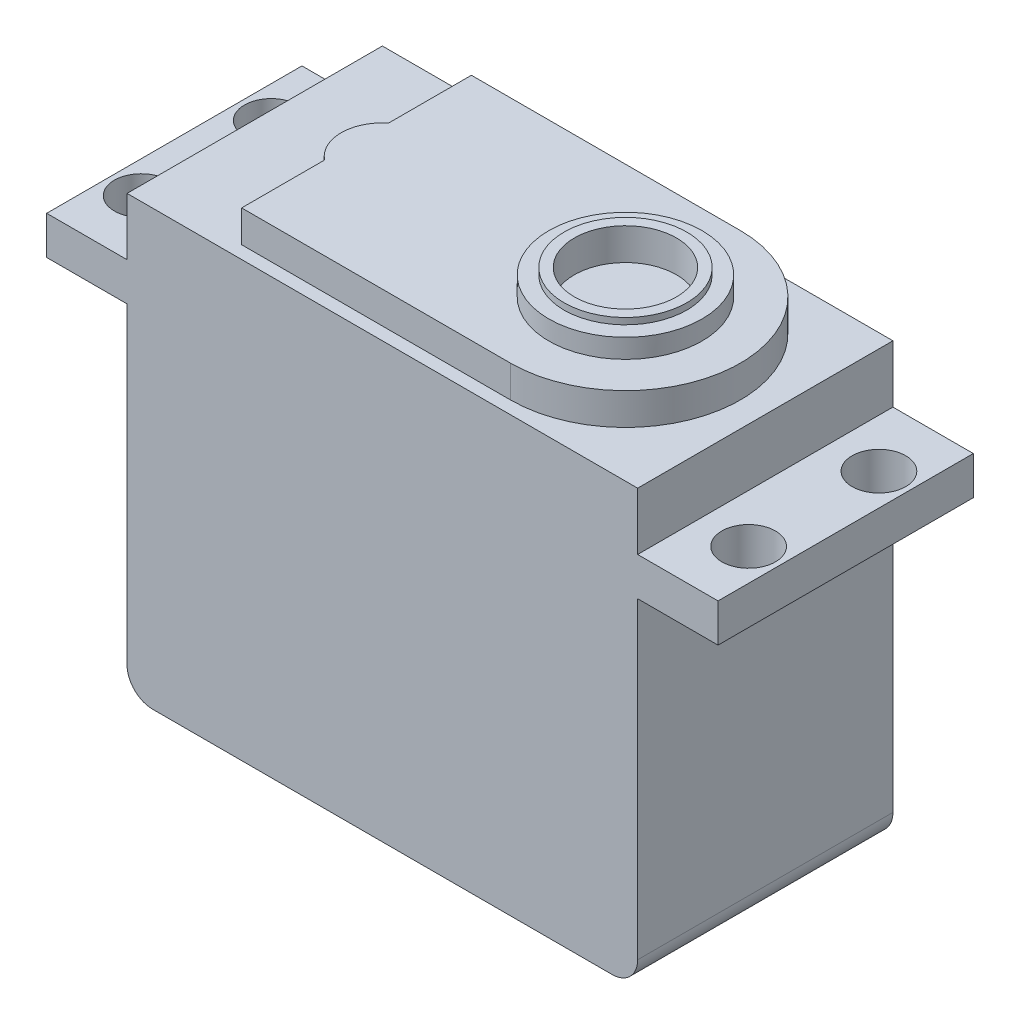
SolidWorks part; units mm, degrees
ref_plane "Front Plane" through (0, 0, 0) normal (0, 0, 1) x (1, 0, 0)
ref_plane "Top Plane" through (0, 0, 0) normal (0, 1, 0) x (1, 0, 0)
ref_plane "Right Plane" through (0, 0, 0) normal (1, 0, 0) x (0, 0, -1)
sketch "Sketch1" plane through (0, 0, 0) normal (0, 0, 1) x (1, 0, 0)
  line L0 (-2, 0) -> (-38, 0)
  line L1 (-40, 2) -> (-40, 26.5)
  line L2 (-40, 26.5) -> (-46.3, 26.5)
  line L3 (-46.3, 26.5) -> (-46.3, 29.5)
  line L4 (-46.3, 29.5) -> (-40, 29.5)
  line L5 (-40, 29.5) -> (-40, 34)
  line L6 (-40, 34) -> (-33, 34)
  line L7 (-33, 34) -> (-33, 36.5)
  line L8 (-33, 36.5) -> (0, 36.5)
  line L9 (0, 36.5) -> (0, 29.5)
  line L10 (0, 29.5) -> (6.3, 29.5)
  line L11 (6.3, 29.5) -> (6.3, 26.5)
  line L12 (6.3, 26.5) -> (0, 26.5)
  line L13 (0, 26.5) -> (0, 2)
  arc A0 (0, 2) -> (-2, 0) centre (-2, 2) cw
  arc A1 (-40, 2) -> (-38, 0) centre (-38, 2) ccw
  point P17 (0, 0)
  point P20 (-40, 0)
  dimension "D10" = 2
  dimension "D1" = 40
  dimension "D2" = 26.5
  dimension "D3" = 6.3
  dimension "D4" = 3
  dimension "D5" = 4.5
  dimension "D6" = 34
  dimension "D7" = 7
  dimension "D8" = 2.5
  dimension "D9" = 6.3
extrude "Boss-Extrude1" add sketch "Sketch1" along normal blind 20
sketch "Sketch2" plane through (0, 29.5, 0) normal (0, 1, 0) x (1, 0, 0)
  line L0 (6.3, -10) -> (3.8, -10) construction
  line L1 (6.3, -20) -> (6.3, 0) construction
  line L2 (3.8, -10) -> (3.8, -20) construction
  line L3 (6.3, -20) -> (0, -20) construction
  line L4 (3.8, -20) -> (3.8, -10) construction
  line L5 (3.8, -10) -> (3.8, 0) construction
  line L6 (6.3, 0) -> (0, 0) construction
  line L7 (3.8, -10) -> (3.8, -15.1034) construction
  line L8 (3.8, -10) -> (3.8, -4.8966) construction
  line L9 (5.9, -15.1034) -> (5.9, -15.8534)
  line L10 (5.9, -15.8534) -> (5.9, -15.1034)
  line L11 (5.9, -15.1034) -> (5.9, -14.3534)
  line L12 (5.9, -15.8534) -> (5.7615, -15.8534)
  line L13 (5.9, -15.8534) -> (6.3, -15.8534)
  line L14 (5.7615, -14.3534) -> (6.3, -14.3534)
  line L15 (6.3, -14.3534) -> (6.3, -15.8534)
  line L16 (5.9, -4.8966) -> (5.9, -2.7966)
  line L17 (5.9, -2.7966) -> (6.3, -2.7966)
  line L18 (5.9, -4.8966) -> (5.9, -6.9966)
  line L19 (5.9, -6.9966) -> (6.3, -6.9966)
  line L20 (5.9, -5.6505) -> (6.3, -5.6505)
  line L21 (5.9, -5.6505) -> (5.76, -5.6505)
  line L22 (5.9, -4.1545) -> (5.7645, -4.1545)
  line L23 (5.9, -4.1545) -> (6.3, -4.1545)
  line L24 (6.3, -4.1545) -> (6.3, -5.6505)
  circle A0 centre (3.8, -15.1034) radius 2.1
  circle A1 centre (3.8, -4.8966) radius 2.1
  dimension "D2" = 4.2
  dimension "D3" = 4.2
  dimension "D1" = 2.5
  dimension "D4" = 0.75
  dimension "D5" = 0.75
extrude "Cut-Extrude1" cut sketch "Sketch2" against normal blind 20 contours A0 | A1
sketch "Sketch3" plane through (0, 29.5, 0) normal (0, 1, 0) x (1, 0, 0)
  line L0 (-46.3, -10) -> (-43.7999, -10)
  line L1 (-46.3, -20) -> (-46.3, 0) construction
  line L2 (-43.7999, -10) -> (-43.7999, 0)
  line L3 (-40, 0) -> (-46.3, 0) construction
  line L4 (-43.7999, -10) -> (-43.7999, -20)
  line L5 (-40, -20) -> (-46.3, -20) construction
  line L6 (-43.7999, -10) -> (-43.7999, -4.9033) construction
  line L7 (-43.7999, -10) -> (-43.7999, -15.0987)
  circle A0 centre (-43.7999, -15.0987) radius 2.098
  circle A1 centre (-43.7999, -4.9033) radius 2.1007
extrude "Cut-Extrude2" cut sketch "Sketch3" against normal blind 20 contours A0 | A1
sketch "Sketch4" plane through (0, 36.5, 0) normal (0, 1, 0) x (1, 0, 0)
  line L3 (-16.5, 0) -> (-16.5, -0.9963) construction
  line L4 (0, 0) -> (-33, 0) construction
  line L5 (-16.5, -20) -> (-16.5, -18.9968) construction
  line L6 (0, -20) -> (-33, -20) construction
  line L7 (-16.5, -18.9968) -> (-32.0272, -18.9968)
  line L8 (-32.0272, -18.9968) -> (-32.0272, -0.9963)
  line L9 (-32.0272, -0.9963) -> (-16.5, -0.9963)
  line L10 (-16.5, -18.9968) -> (-10.955, -18.9968)
  line L11 (-16.5, -0.9963) -> (-10.955, -0.9963)
  arc A0 (-10.955, -18.9968) -> (-10.955, -1.0032) centre (-10.955, -10) ccw
sketch "Sketch7" plane through (0, 36.5, 0) normal (0, 1, 0) x (1, 0, 0)
  circle A0 centre (-10.955, -10) radius 6
  dimension "D1" = 12
extrude "Boss-Extrude2" add sketch "Sketch7" along normal blind 1.5
sketch "Sketch8" plane through (0, 38, 0) normal (0, 1, 0) x (1, 0, 0)
  line L0 (-16.943, -10.38) -> (-4.967, -9.62) construction
  circle A0 centre (-10.955, -10) radius 6 construction
  circle A1 centre (-10.955, -10) radius 4.8049
extrude "Boss-Extrude3" add sketch "Sketch8" along normal blind 0.5
sketch "Sketch9" plane through (0, 38.5, 0) normal (0, 1, 0) x (1, 0, 0)
  line L0 (-10.955, -14.8049) -> (-10.955, -5.1951) construction
  circle A0 centre (-10.955, -10) radius 4.8049 construction
  circle A1 centre (-10.955, -10) radius 4.0026
extrude "Cut-Extrude5" cut sketch "Sketch9" against normal blind 2.5
sketch "Sketch10" plane through (0, 36.5, 0) normal (0, 1, 0) x (1, 0, 0)
  line L0 (-32.0272, -18.9968) -> (-10.955, -18.9968)
  line L1 (-32.0272, -18.9968) -> (-32.0272, -0.9963)
  line L2 (-32.0272, -0.9963) -> (-10.955, -0.9963)
  arc A0 (-10.955, -0.9963) -> (-10.955, -18.9968) centre (-10.955, -9.9965) cw
extrude "Cut-Extrude6" cut sketch "Sketch10" against normal blind 2.5 flip side to cut
sketch "Sketch11" plane through (0, 36.5, 0) normal (0, 1, 0) x (1, 0, 0)
  line L0 (-32.0272, -0.9963) -> (-32.0272, -18.9968) construction
  line L1 (-32.0272, -9.9965) -> (-33.2305, -9.9965)
  line L2 (-32.0272, -9.9965) -> (-30.0194, -9.9965)
  line L3 (-32.0272, -12.5025) -> (-32.0272, -7.4905)
  arc A0 (-33.2305, -9.9965) -> (-32.0272, -7.4905) centre (-30.0194, -9.9965) cw
  arc A1 (-33.2305, -9.9965) -> (-32.0272, -12.5025) centre (-30.0194, -9.9965) ccw
extrude "Boss-Extrude4" add sketch "Sketch11" against normal blind 2.5 contours A1 L3 A0
